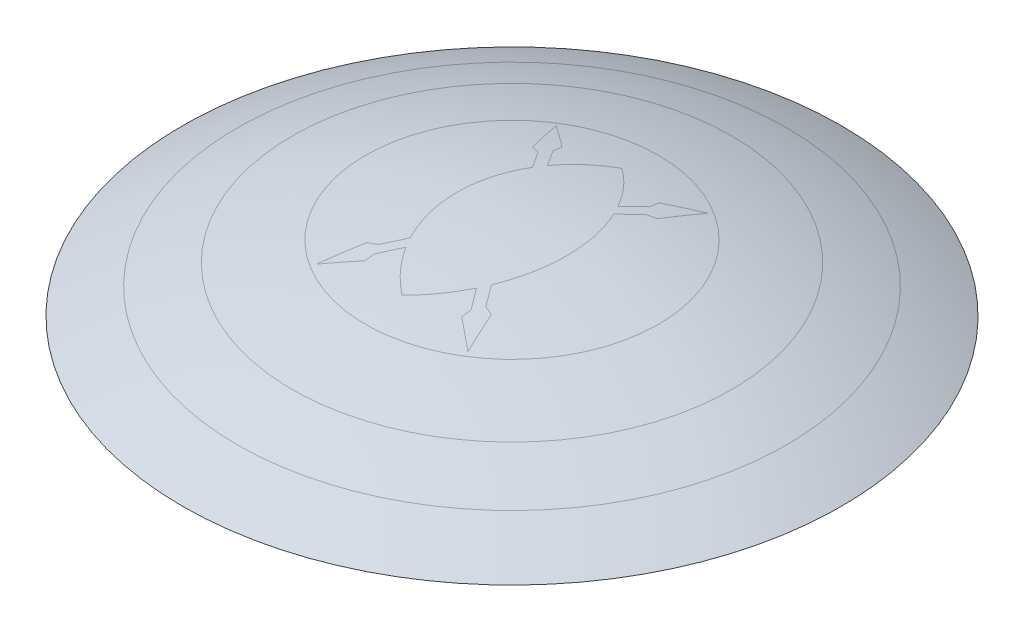
SolidWorks part; units mm, degrees
material "Plain Carbon Steel"
ref_plane "Front Plane" through (0, 0, 0) normal (0, 0, 1) x (1, 0, 0)
ref_plane "Top Plane" through (0, 0, 0) normal (0, 1, 0) x (1, 0, 0)
ref_plane "Right Plane" through (0, 0, 0) normal (1, 0, 0) x (0, 0, -1)
sketch "Sketch2" plane through (0, 0, 0) normal (0, 0, 1) x (1, 0, 0)
  line L0 (0, 0) -> (0, 90)
  line L1 (0, 0) -> (360, 0)
  arc A0 (0, 90) -> (360, 0) centre (-8.7381, -709.9523) cw
  dimension "D3" = 800
  dimension "D1" = 360
  dimension "D2" = 90
revolve "Revolve1" add sketch "Sketch2" angle 360 about L0
ref_plane "Plane1" through (0, 90, 0) normal (0, -1, 0) x (-1, 0, 0)
sketch "Sketch3" plane through (0, 90, 0) normal (0, -1, 0) x (-1, 0, 0)
  line L35 (0, 120) -> (0, -120) construction
  line L37 (-44.3357, 66.7377) -> (-58.6751, 87.2165)
  line L38 (-38.5711, 77.2623) -> (-52.9105, 97.7411)
  line L39 (-52.9105, 97.7411) -> (-52.9105, 107.7411)
  line L40 (-58.6751, 87.2165) -> (-68.0721, 90.6367)
  line L41 (-38.5711, 77.2623) -> (-44.3357, 66.7377) construction
  line L42 (-52.9105, 107.7411) -> (-82.7509, 130.9789)
  line L43 (-82.7509, 130.9789) -> (-68.0721, 90.6367)
  line L44 (-82.7509, 130.9789) -> (-41.4534, 72) construction
  line L45 (-52.9105, 97.7411) -> (-58.6751, 87.2165) construction
  line L46 (0, 0) -> (-60, 0) construction
  line L47 (82.7509, 130.9789) -> (41.4534, 72) construction
  line L48 (38.5711, 77.2623) -> (44.3357, 66.7377) construction
  line L49 (52.9105, 97.7411) -> (58.6751, 87.2165) construction
  line L50 (82.7509, 130.9789) -> (68.0721, 90.6367)
  line L51 (52.9105, 107.7411) -> (82.7509, 130.9789)
  line L52 (58.6751, 87.2165) -> (68.0721, 90.6367)
  line L53 (52.9105, 97.7411) -> (52.9105, 107.7411)
  line L54 (38.5711, 77.2623) -> (52.9105, 97.7411)
  line L55 (44.3357, 66.7377) -> (58.6751, 87.2165)
  line L56 (38.5711, -77.2623) -> (44.3357, -66.7377) construction
  line L57 (82.7509, -130.9789) -> (41.4534, -72) construction
  line L58 (-82.7509, -130.9789) -> (-41.4534, -72) construction
  line L59 (-38.5711, -77.2623) -> (-44.3357, -66.7377) construction
  line L60 (44.3357, -66.7377) -> (58.6751, -87.2165)
  line L61 (38.5711, -77.2623) -> (52.9105, -97.7411)
  line L62 (52.9105, -97.7411) -> (52.9105, -107.7411)
  line L63 (58.6751, -87.2165) -> (68.0721, -90.6367)
  line L64 (52.9105, -107.7411) -> (82.7509, -130.9789)
  line L65 (82.7509, -130.9789) -> (68.0721, -90.6367)
  line L66 (52.9105, -97.7411) -> (58.6751, -87.2165) construction
  line L67 (-52.9105, -97.7411) -> (-58.6751, -87.2165) construction
  line L68 (-82.7509, -130.9789) -> (-68.0721, -90.6367)
  line L69 (-52.9105, -107.7411) -> (-82.7509, -130.9789)
  line L70 (-58.6751, -87.2165) -> (-68.0721, -90.6367)
  line L71 (-52.9105, -97.7411) -> (-52.9105, -107.7411)
  line L72 (-38.5711, -77.2623) -> (-52.9105, -97.7411)
  line L73 (-44.3357, -66.7377) -> (-58.6751, -87.2165)
  circle A0 centre (0, 0) radius 300
  circle A1 centre (0, 0) radius 240
  circle A2 centre (0, 0) radius 160
  arc A5 (0, 120) -> (-38.5711, 77.2623) centre (90, 0) ccw
  arc A6 (0, 120) -> (38.5711, 77.2623) centre (-90, 0) cw
  arc A7 (38.5711, -77.2623) -> (0, -120) centre (-90, 0) cw
  arc A8 (-38.5711, -77.2623) -> (0, -120) centre (90, 0) ccw
  arc A9 (-44.3357, 66.7377) -> (-44.3357, -66.7377) centre (90, 0) ccw
  arc A10 (44.3357, 66.7377) -> (44.3357, -66.7377) centre (-90, 0) cw
  dimension "D1" = 600
  dimension "D2" = 480
  dimension "D3" = 240
  dimension "D4" = 320
  dimension "D6" = 72
  dimension "D7" = 12
  dimension "D8" = 25
  dimension "D9" = 72
  dimension "D10" = 55
  dimension "D11" = 10
  dimension "D12" = 145
  dimension "D13" = 145
split line "Split Line1"
shell "Shell1" thickness 10
